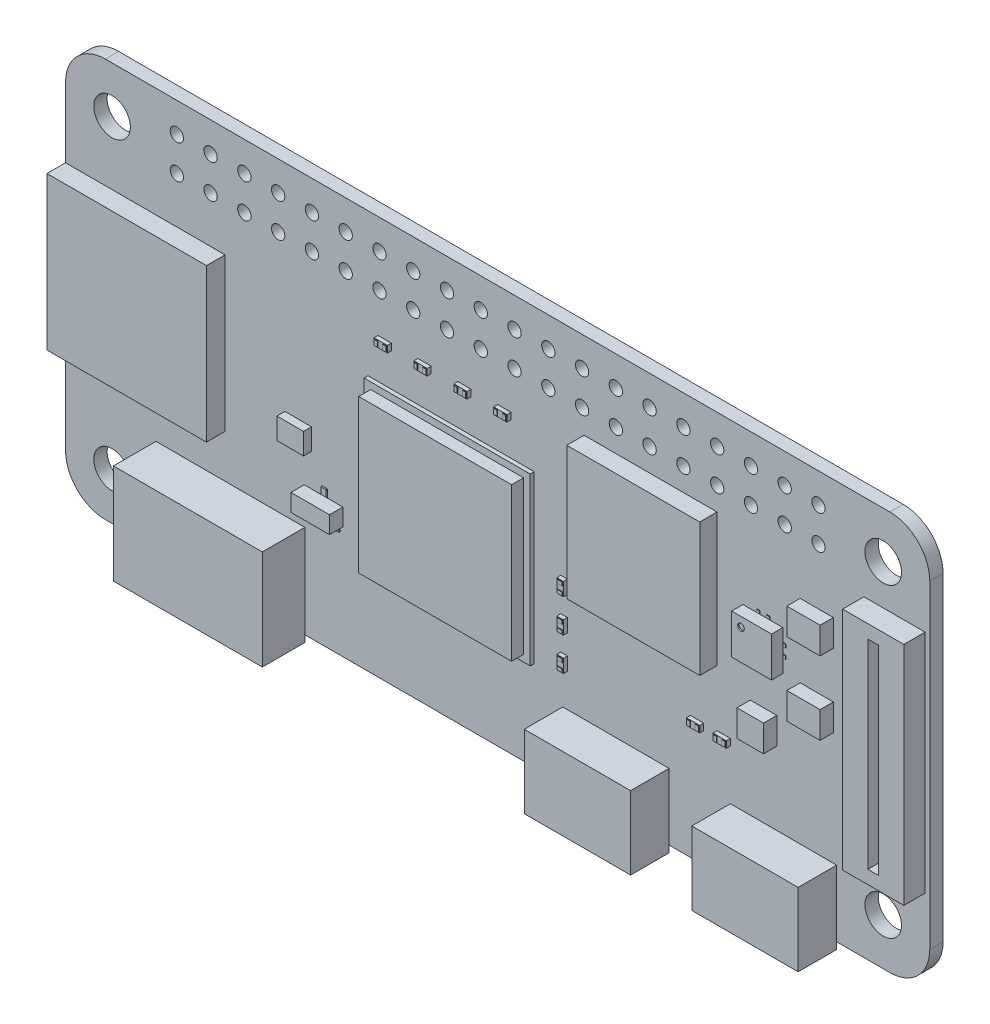
SolidWorks part; units mm, degrees
ref_plane "Front Plane" through (0, 0, 0) normal (0, 0, 1) x (1, 0, 0)
ref_plane "Top Plane" through (0, 0, 0) normal (0, 1, 0) x (1, 0, 0)
ref_plane "Right Plane" through (0, 0, 0) normal (1, 0, 0) x (0, 0, -1)
sketch "Sketch1" plane through (0, 0, 0) normal (0, 0, 1) x (1, 0, 0)
  line L0 (3, 0) -> (62, 0)
  line L1 (65, 3) -> (65, 27)
  line L2 (62, 30) -> (3, 30)
  line L3 (0, 27) -> (0, 3)
  arc A0 (62, 0) -> (65, 3) centre (62, 3) ccw
  arc A1 (65, 27) -> (62, 30) centre (62, 27) ccw
  arc A2 (3, 30) -> (0, 27) centre (3, 27) ccw
  arc A3 (0, 3) -> (3, 0) centre (3, 3) ccw
extrude "PCB" add sketch "Sketch1" along normal blind 1
ref_plane "Plane_z1" through (0, 0, 1) normal (0, 0, 1) x (1, 0, 0)
sketch "Sketch2" plane through (0, 0, 1) normal (0, 0, 1) x (1, 0, 0)
  line L1 (52, 15.3) -> (52.25, 15.3)
  line L2 (52, 15.3) -> (52, 15.6)
  line L3 (52, 15.6) -> (52.25, 15.6)
  line L4 (52.25, 15.3) -> (52.25, 15.6)
  line L6 (50.8, 16.5) -> (51.1, 16.5)
  line L7 (50.8, 16.5) -> (50.8, 16.75)
  line L8 (50.8, 16.75) -> (51.1, 16.75)
  line L9 (51.1, 16.5) -> (51.1, 16.75)
  line L11 (52, 18.4) -> (52.25, 18.4)
  line L12 (52, 18.4) -> (52, 18.7)
  line L13 (52, 18.7) -> (52.25, 18.7)
  line L14 (52.25, 18.4) -> (52.25, 18.7)
  line L16 (53.9, 16.5) -> (54.2, 16.5)
  line L17 (53.9, 16.5) -> (53.9, 16.75)
  line L18 (53.9, 16.75) -> (54.2, 16.75)
  line L19 (54.2, 16.5) -> (54.2, 16.75)
  line L21 (52.75, 15.3) -> (53, 15.3)
  line L22 (52.75, 15.3) -> (52.75, 15.6)
  line L23 (52.75, 15.6) -> (53, 15.6)
  line L24 (53, 15.3) -> (53, 15.6)
  line L26 (50.8, 17.25) -> (51.1, 17.25)
  line L27 (50.8, 17.25) -> (50.8, 17.5)
  line L28 (50.8, 17.5) -> (51.1, 17.5)
  line L29 (51.1, 17.25) -> (51.1, 17.5)
  line L31 (52.75, 18.4) -> (53, 18.4)
  line L32 (52.75, 18.4) -> (52.75, 18.7)
  line L33 (52.75, 18.7) -> (53, 18.7)
  line L34 (53, 18.4) -> (53, 18.7)
  line L36 (53.9, 17.25) -> (54.2, 17.25)
  line L37 (53.9, 17.25) -> (53.9, 17.5)
  line L38 (53.9, 17.5) -> (54.2, 17.5)
  line L39 (54.2, 17.25) -> (54.2, 17.5)
extrude "SMD_add00" add sketch "Sketch2" along normal blind 0.05
sketch "Sketch3" plane through (0, 0, 1) normal (0, 0, 1) x (1, 0, 0)
  line L1 (18.35, 8.05) -> (18.75, 8.05)
  line L2 (18.35, 8.05) -> (18.35, 8.75)
  line L3 (18.35, 8.75) -> (18.75, 8.75)
  line L4 (18.75, 8.05) -> (18.75, 8.75)
  line L6 (20.25, 8.05) -> (20.65, 8.05)
  line L7 (20.25, 8.05) -> (20.25, 8.75)
  line L8 (20.25, 8.75) -> (20.65, 8.75)
  line L9 (20.65, 8.05) -> (20.65, 8.75)
  line L11 (19.3, 9.65) -> (19.7, 9.65)
  line L12 (19.3, 9.65) -> (19.3, 10.35)
  line L13 (19.3, 10.35) -> (19.7, 10.35)
  line L14 (19.7, 9.65) -> (19.7, 10.35)
extrude "SMD_add01" add sketch "Sketch3" along normal blind 0.1
sketch "Sketch4" plane through (0, 0, 1) normal (0, 0, 1) x (1, 0, 0)
  line L1 (22.75, 6.75) -> (35.25, 6.75)
  line L2 (22.75, 6.75) -> (22.75, 19.25)
  line L3 (22.75, 19.25) -> (35.25, 19.25)
  line L4 (35.25, 6.75) -> (35.25, 19.25)
  line L6 (37.25, 7.5) -> (37.75, 7.5)
  line L7 (37.25, 7.5) -> (37.25, 8.5)
  line L8 (37.25, 8.5) -> (37.75, 8.5)
  line L9 (37.75, 7.5) -> (37.75, 8.5)
  line L11 (37.25, 10) -> (37.75, 10)
  line L12 (37.25, 10) -> (37.25, 11)
  line L13 (37.25, 11) -> (37.75, 11)
  line L14 (37.75, 10) -> (37.75, 11)
  line L16 (37.25, 12.5) -> (37.75, 12.5)
  line L17 (37.25, 12.5) -> (37.25, 13.5)
  line L18 (37.25, 13.5) -> (37.75, 13.5)
  line L19 (37.75, 12.5) -> (37.75, 13.5)
  line L21 (47, 8.75) -> (48, 8.75)
  line L22 (47, 8.75) -> (47, 9.25)
  line L23 (47, 9.25) -> (48, 9.25)
  line L24 (48, 8.75) -> (48, 9.25)
  line L26 (49, 8.75) -> (50, 8.75)
  line L27 (49, 8.75) -> (49, 9.25)
  line L28 (49, 9.25) -> (50, 9.25)
  line L29 (50, 8.75) -> (50, 9.25)
  line L31 (23.5, 21.75) -> (24.5, 21.75)
  line L32 (23.5, 21.75) -> (23.5, 22.25)
  line L33 (23.5, 22.25) -> (24.5, 22.25)
  line L34 (24.5, 21.75) -> (24.5, 22.25)
  line L36 (26.5, 21.75) -> (27.5, 21.75)
  line L37 (26.5, 21.75) -> (26.5, 22.25)
  line L38 (26.5, 22.25) -> (27.5, 22.25)
  line L39 (27.5, 21.75) -> (27.5, 22.25)
  line L41 (29.5, 21.75) -> (30.5, 21.75)
  line L42 (29.5, 21.75) -> (29.5, 22.25)
  line L43 (29.5, 22.25) -> (30.5, 22.25)
  line L44 (30.5, 21.75) -> (30.5, 22.25)
  line L46 (32.5, 21.75) -> (33.5, 21.75)
  line L47 (32.5, 21.75) -> (32.5, 22.25)
  line L48 (32.5, 22.25) -> (33.5, 22.25)
  line L49 (33.5, 21.75) -> (33.5, 22.25)
extrude "SMD_add02" add sketch "Sketch4" along normal blind 0.3
sketch "Sketch5" plane through (0, 0, 1) normal (0, 0, 1) x (1, 0, 0)
  line L1 (16.5, 12.2) -> (18.5, 12.2)
  line L2 (16.5, 12.2) -> (16.5, 13.8)
  line L3 (16.5, 13.8) -> (18.5, 13.8)
  line L4 (18.5, 12.2) -> (18.5, 13.8)
extrude "SMD_add03" add sketch "Sketch5" along normal blind 0.6
sketch "Sketch6" plane through (0, 0, 1) normal (0, 0, 1) x (1, 0, 0)
  line L1 (55.25, 19) -> (57.75, 19)
  line L2 (55.25, 19) -> (55.25, 21)
  line L3 (55.25, 21) -> (57.75, 21)
  line L4 (57.75, 19) -> (57.75, 21)
  line L6 (55.25, 13.5) -> (57.75, 13.5)
  line L7 (55.25, 13.5) -> (55.25, 15.5)
  line L8 (55.25, 15.5) -> (57.75, 15.5)
  line L9 (57.75, 13.5) -> (57.75, 15.5)
  line L11 (51.5, 10.5) -> (53.5, 10.5)
  line L12 (51.5, 10.5) -> (51.5, 12.5)
  line L13 (51.5, 12.5) -> (53.5, 12.5)
  line L14 (53.5, 10.5) -> (53.5, 12.5)
extrude "SMD_add04" add sketch "Sketch6" along normal blind 1
sketch "Sketch7" plane through (0, 0, 1) normal (0, 0, 1) x (1, 0, 0)
  line L1 (39, 13.5) -> (49, 13.5)
  line L2 (39, 13.5) -> (39, 23.5)
  line L3 (39, 23.5) -> (49, 23.5)
  line L4 (49, 13.5) -> (49, 23.5)
extrude "SMD_add05" add sketch "Sketch7" along normal blind 1.3
sketch "Sketch8" plane through (0, 0, 1) normal (0, 0, 1) x (1, 0, 0)
  line L1 (0, 10.25) -> (12, 10.25)
  line L2 (0, 10.25) -> (0, 21.75)
  line L3 (0, 21.75) -> (12, 21.75)
  line L4 (12, 10.25) -> (12, 21.75)
extrude "SMD_add06" add sketch "Sketch8" along normal blind 1.4
sketch "Sketch9" plane through (0, 0, 1) normal (0, 0, 1) x (1, 0, 0)
  line L1 (60.05, 6.5) -> (64.65, 6.5)
  line L2 (60.05, 6.5) -> (60.05, 23.5)
  line L3 (60.05, 23.5) -> (64.65, 23.5)
  line L4 (64.65, 6.5) -> (64.65, 23.5)
extrude "SMD_add07" add sketch "Sketch9" along normal blind 1.6
sketch "Sketch10" plane through (0, 0, 1) normal (0, 0, 1) x (1, 0, 0)
  line L1 (37.4, -0.5) -> (45.4, -0.5)
  line L2 (37.4, -0.5) -> (37.4, 5)
  line L3 (37.4, 5) -> (45.4, 5)
  line L4 (45.4, -0.5) -> (45.4, 5)
  line L6 (50, -0.5) -> (58, -0.5)
  line L7 (50, -0.5) -> (50, 5)
  line L8 (50, 5) -> (58, 5)
  line L9 (58, -0.5) -> (58, 5)
extrude "SMD_add08" add sketch "Sketch10" along normal blind 2.9
sketch "Sketch11" plane through (0, 0, 1) normal (0, 0, 1) x (1, 0, 0)
  line L1 (6.8, -0.5) -> (18, -0.5)
  line L2 (6.8, -0.5) -> (6.8, 7)
  line L3 (6.8, 7) -> (18, 7)
  line L4 (18, -0.5) -> (18, 7)
extrude "SMD_add09" add sketch "Sketch11" along normal blind 3.2
ref_plane "Plane_z1_05" through (0, 0, 1.05) normal (0, 0, 1) x (1, 0, 0)
sketch "Sketch12" plane through (0, 0, 1.05) normal (0, 0, 1) x (1, 0, 0)
  line L1 (51, 15.5) -> (54, 15.5)
  line L2 (51, 15.5) -> (51, 18.5)
  line L3 (51, 18.5) -> (54, 18.5)
  line L4 (54, 15.5) -> (54, 18.5)
extrude "SMD_add10" add sketch "Sketch12" along normal blind 0.85
ref_plane "Plane_z1_1" through (0, 0, 1.1) normal (0, 0, 1) x (1, 0, 0)
sketch "Sketch13" plane through (0, 0, 1.1) normal (0, 0, 1) x (1, 0, 0)
  line L1 (18.05, 8.55) -> (20.95, 8.55)
  line L2 (18.05, 8.55) -> (18.05, 9.85)
  line L3 (18.05, 9.85) -> (20.95, 9.85)
  line L4 (20.95, 8.55) -> (20.95, 9.85)
extrude "SMD_add11" add sketch "Sketch13" along normal blind 1
ref_plane "Plane_z1_3" through (0, 0, 1.3) normal (0, 0, 1) x (1, 0, 0)
sketch "Sketch14" plane through (0, 0, 1.3) normal (0, 0, 1) x (1, 0, 0)
  line L1 (37.3, 7.55) -> (37.7, 7.55)
  line L2 (37.3, 7.55) -> (37.3, 7.8)
  line L3 (37.3, 7.8) -> (37.7, 7.8)
  line L4 (37.7, 7.55) -> (37.7, 7.8)
  line L6 (37.3, 8.2) -> (37.7, 8.2)
  line L7 (37.3, 8.2) -> (37.3, 8.45)
  line L8 (37.3, 8.45) -> (37.7, 8.45)
  line L9 (37.7, 8.2) -> (37.7, 8.45)
  line L11 (37.3, 10.05) -> (37.7, 10.05)
  line L12 (37.3, 10.05) -> (37.3, 10.3)
  line L13 (37.3, 10.3) -> (37.7, 10.3)
  line L14 (37.7, 10.05) -> (37.7, 10.3)
  line L16 (37.3, 10.7) -> (37.7, 10.7)
  line L17 (37.3, 10.7) -> (37.3, 10.95)
  line L18 (37.3, 10.95) -> (37.7, 10.95)
  line L19 (37.7, 10.7) -> (37.7, 10.95)
  line L21 (37.3, 12.55) -> (37.7, 12.55)
  line L22 (37.3, 12.55) -> (37.3, 12.8)
  line L23 (37.3, 12.8) -> (37.7, 12.8)
  line L24 (37.7, 12.55) -> (37.7, 12.8)
  line L26 (37.3, 13.2) -> (37.7, 13.2)
  line L27 (37.3, 13.2) -> (37.3, 13.45)
  line L28 (37.3, 13.45) -> (37.7, 13.45)
  line L29 (37.7, 13.2) -> (37.7, 13.45)
  line L31 (47.05, 8.8) -> (47.3, 8.8)
  line L32 (47.05, 8.8) -> (47.05, 9.2)
  line L33 (47.05, 9.2) -> (47.3, 9.2)
  line L34 (47.3, 8.8) -> (47.3, 9.2)
  line L36 (47.7, 8.8) -> (47.95, 8.8)
  line L37 (47.7, 8.8) -> (47.7, 9.2)
  line L38 (47.7, 9.2) -> (47.95, 9.2)
  line L39 (47.95, 8.8) -> (47.95, 9.2)
  line L41 (49.05, 8.8) -> (49.3, 8.8)
  line L42 (49.05, 8.8) -> (49.05, 9.2)
  line L43 (49.05, 9.2) -> (49.3, 9.2)
  line L44 (49.3, 8.8) -> (49.3, 9.2)
  line L46 (49.7, 8.8) -> (49.95, 8.8)
  line L47 (49.7, 8.8) -> (49.7, 9.2)
  line L48 (49.7, 9.2) -> (49.95, 9.2)
  line L49 (49.95, 8.8) -> (49.95, 9.2)
  line L51 (23.55, 21.8) -> (23.8, 21.8)
  line L52 (23.55, 21.8) -> (23.55, 22.2)
  line L53 (23.55, 22.2) -> (23.8, 22.2)
  line L54 (23.8, 21.8) -> (23.8, 22.2)
  line L56 (24.2, 21.8) -> (24.45, 21.8)
  line L57 (24.2, 21.8) -> (24.2, 22.2)
  line L58 (24.2, 22.2) -> (24.45, 22.2)
  line L59 (24.45, 21.8) -> (24.45, 22.2)
  line L61 (26.55, 21.8) -> (26.8, 21.8)
  line L62 (26.55, 21.8) -> (26.55, 22.2)
  line L63 (26.55, 22.2) -> (26.8, 22.2)
  line L64 (26.8, 21.8) -> (26.8, 22.2)
  line L66 (27.2, 21.8) -> (27.45, 21.8)
  line L67 (27.2, 21.8) -> (27.2, 22.2)
  line L68 (27.2, 22.2) -> (27.45, 22.2)
  line L69 (27.45, 21.8) -> (27.45, 22.2)
  line L71 (29.55, 21.8) -> (29.8, 21.8)
  line L72 (29.55, 21.8) -> (29.55, 22.2)
  line L73 (29.55, 22.2) -> (29.8, 22.2)
  line L74 (29.8, 21.8) -> (29.8, 22.2)
  line L76 (30.2, 21.8) -> (30.45, 21.8)
  line L77 (30.2, 21.8) -> (30.2, 22.2)
  line L78 (30.2, 22.2) -> (30.45, 22.2)
  line L79 (30.45, 21.8) -> (30.45, 22.2)
  line L81 (32.55, 21.8) -> (32.8, 21.8)
  line L82 (32.55, 21.8) -> (32.55, 22.2)
  line L83 (32.55, 22.2) -> (32.8, 22.2)
  line L84 (32.8, 21.8) -> (32.8, 22.2)
  line L86 (33.2, 21.8) -> (33.45, 21.8)
  line L87 (33.2, 21.8) -> (33.2, 22.2)
  line L88 (33.2, 22.2) -> (33.45, 22.2)
  line L89 (33.45, 21.8) -> (33.45, 22.2)
extrude "SMD_add12" add sketch "Sketch14" along normal blind 0.05
sketch "Sketch15" plane through (0, 0, 1.3) normal (0, 0, 1) x (1, 0, 0)
  line L1 (23.25, 7.25) -> (34.75, 7.25)
  line L2 (23.25, 7.25) -> (23.25, 18.75)
  line L3 (23.25, 18.75) -> (34.75, 18.75)
  line L4 (34.75, 7.25) -> (34.75, 18.75)
extrude "SMD_add13" add sketch "Sketch15" along normal blind 0.9
ref_plane "Plane_ym0_5" through (0, -0.5, 0) normal (0, 1, 0) x (1, 0, 0)
sketch "Sketch16" plane through (0, -0.5, 0) normal (0, 1, 0) x (1, 0, 0)
  line L1 (10.3, -2.3) -> (14.5, -2.3)
  line L2 (10.3, -2.3) -> (10.3, -2.9)
  line L3 (10.3, -2.9) -> (14.5, -2.9)
  line L4 (14.5, -2.3) -> (14.5, -2.9)
extrude "SMD_cut00" cut sketch "Sketch16" along normal blind 0.5
ref_plane "Plane_y6_5" through (0, 6.5, 0) normal (0, 1, 0) x (1, 0, 0)
sketch "Sketch17" plane through (0, 6.5, 0) normal (0, 1, 0) x (1, 0, 0)
  line L1 (9.65, -1.6) -> (15.15, -1.6)
  line L2 (9.65, -1.6) -> (9.65, -3.6)
  line L3 (9.65, -3.6) -> (15.15, -3.6)
  line L4 (15.15, -1.6) -> (15.15, -3.6)
  line L6 (10.3, -2.3) -> (14.5, -2.3)
  line L7 (10.3, -2.3) -> (10.3, -2.9)
  line L8 (10.3, -2.9) -> (14.5, -2.9)
  line L9 (14.5, -2.3) -> (14.5, -2.9)
extrude "SMD_cut01" cut sketch "Sketch17" against normal blind 7
ref_plane "Plane_z1_9" through (0, 0, 1.9) normal (0, 0, 1) x (1, 0, 0)
sketch "Sketch18" plane through (0, 0, 1.9) normal (0, 0, 1) x (1, 0, 0)
  circle A0 centre (51.7, 17.8) radius 0.25
extrude "SMD_cut02" cut sketch "Sketch18" against normal blind 0.1
ref_plane "Plane_z2_6" through (0, 0, 2.6) normal (0, 0, 1) x (1, 0, 0)
sketch "Sketch19" plane through (0, 0, 2.6) normal (0, 0, 1) x (1, 0, 0)
  line L1 (61.95, 7.5) -> (62.75, 7.5)
  line L2 (61.95, 7.5) -> (61.95, 22.5)
  line L3 (61.95, 22.5) -> (62.75, 22.5)
  line L4 (62.75, 7.5) -> (62.75, 22.5)
extrude "SMD_cut03" cut sketch "Sketch19" against normal blind 1.1
sketch "Sketch20" plane through (0, 0, 1) normal (0, 0, 1) x (1, 0, 0)
  circle A0 centre (3.5, 3.5) radius 1.375
  circle A1 centre (61.5, 3.5) radius 1.375
  circle A2 centre (3.5, 26.5) radius 1.375
  circle A3 centre (61.5, 26.5) radius 1.375
  circle A4 centre (8.37, 25.23) radius 0.5
  circle A5 centre (8.37, 27.77) radius 0.5
  circle A6 centre (10.91, 25.23) radius 0.5
  circle A7 centre (10.91, 27.77) radius 0.5
  circle A8 centre (13.45, 25.23) radius 0.5
  circle A9 centre (13.45, 27.77) radius 0.5
  circle A10 centre (15.99, 25.23) radius 0.5
  circle A11 centre (15.99, 27.77) radius 0.5
  circle A12 centre (18.53, 25.23) radius 0.5
  circle A13 centre (18.53, 27.77) radius 0.5
  circle A14 centre (21.07, 25.23) radius 0.5
  circle A15 centre (21.07, 27.77) radius 0.5
  circle A16 centre (23.61, 25.23) radius 0.5
  circle A17 centre (23.61, 27.77) radius 0.5
  circle A18 centre (26.15, 25.23) radius 0.5
  circle A19 centre (26.15, 27.77) radius 0.5
  circle A20 centre (28.69, 25.23) radius 0.5
  circle A21 centre (28.69, 27.77) radius 0.5
  circle A22 centre (31.23, 25.23) radius 0.5
  circle A23 centre (31.23, 27.77) radius 0.5
  circle A24 centre (33.77, 25.23) radius 0.5
  circle A25 centre (33.77, 27.77) radius 0.5
  circle A26 centre (36.31, 25.23) radius 0.5
  circle A27 centre (36.31, 27.77) radius 0.5
  circle A28 centre (38.85, 25.23) radius 0.5
  circle A29 centre (38.85, 27.77) radius 0.5
  circle A30 centre (41.39, 25.23) radius 0.5
  circle A31 centre (41.39, 27.77) radius 0.5
  circle A32 centre (43.93, 25.23) radius 0.5
  circle A33 centre (43.93, 27.77) radius 0.5
  circle A34 centre (46.47, 25.23) radius 0.5
  circle A35 centre (46.47, 27.77) radius 0.5
  circle A36 centre (49.01, 25.23) radius 0.5
  circle A37 centre (49.01, 27.77) radius 0.5
  circle A38 centre (51.55, 25.23) radius 0.5
  circle A39 centre (51.55, 27.77) radius 0.5
  circle A40 centre (54.09, 25.23) radius 0.5
  circle A41 centre (54.09, 27.77) radius 0.5
  circle A42 centre (56.63, 25.23) radius 0.5
  circle A43 centre (56.63, 27.77) radius 0.5
extrude "Holes" cut sketch "Sketch20" against normal blind 1
equation "\"pcb_t\" = 1.0mm"
equation "\"D1@PCB\" = \"pcb_t\""
